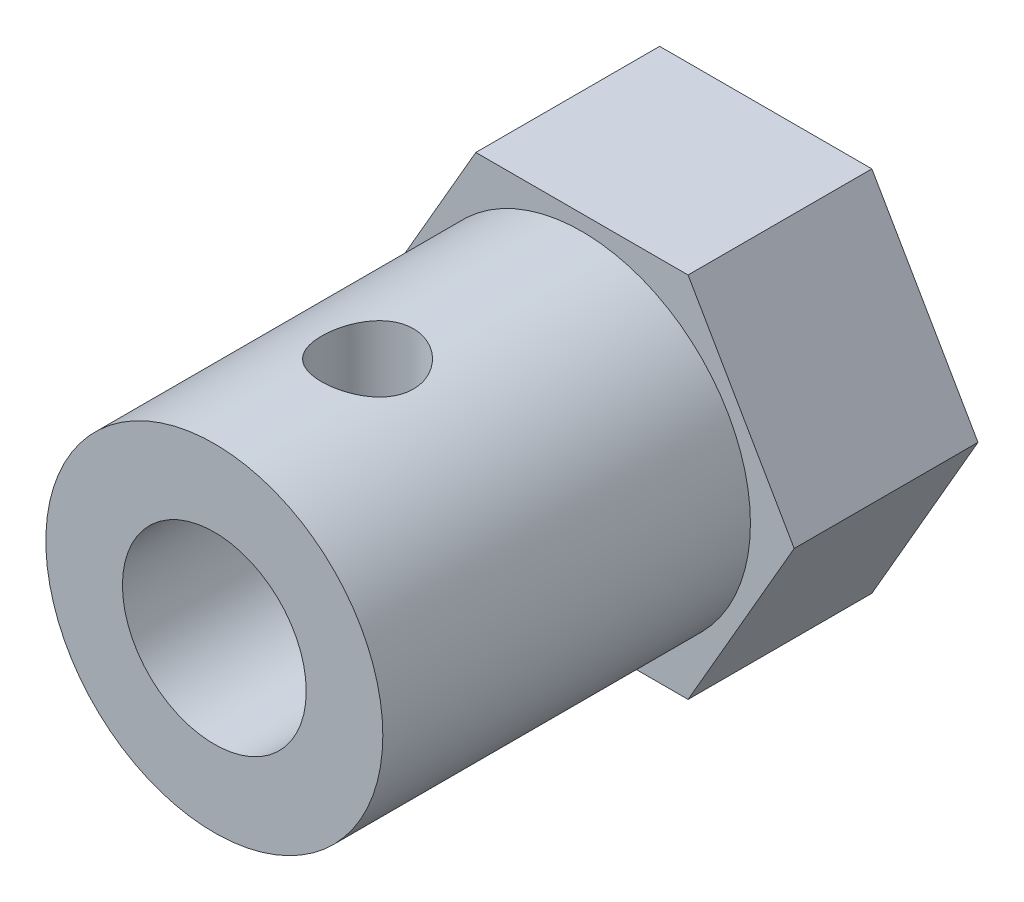
SolidWorks part; units mm, degrees
ref_plane "前视基准面" through (0, 0, 0) normal (0, 0, 1) x (1, 0, 0)
ref_plane "上视基准面" through (0, 0, 0) normal (0, 1, 0) x (1, 0, 0)
ref_plane "右视基准面" through (0, 0, 0) normal (1, 0, 0) x (0, 0, -1)
sketch "草图1" plane through (0, 0, 0) normal (0, 0, 1) x (1, 0, 0)
  line L1 (6.9282, 0) -> (3.4641, 6)
  line L2 (3.4641, 6) -> (-3.4641, 6)
  line L3 (-3.4641, 6) -> (-6.9282, 0)
  line L4 (-6.9282, 0) -> (-3.4641, -6)
  line L5 (-3.4641, -6) -> (3.4641, -6)
  line L6 (3.4641, -6) -> (6.9282, 0)
  circle A0 centre (0, 0) radius 6 construction
extrude "凸台-拉伸1" add sketch "草图1" along normal blind 6
sketch "草图2" plane through (0, 0, 6) normal (0, 0, 1) x (1, 0, 0)
  circle A0 centre (0, 0) radius 5.5
extrude "凸台-拉伸2" add sketch "草图2" along normal blind 12
sketch "草图3" plane through (0, 0, 18) normal (0, 0, 1) x (1, 0, 0)
  circle A0 centre (0, 0) radius 3
extrude "切除-拉伸1" cut sketch "草图3" against normal blind 13
sketch "草图4" plane through (0, 0, 0) normal (0, 0, -1) x (-1, 0, 0)
  circle A0 centre (0, 0) radius 2
extrude "切除-拉伸2" cut sketch "草图4" against normal blind 5
sketch "草图5" plane through (0, 0, 0) normal (0, 1, 0) x (1, 0, 0)
  circle A0 centre (0, -13) radius 1.5
extrude "切除-拉伸3" cut sketch "草图5" along normal blind 12
